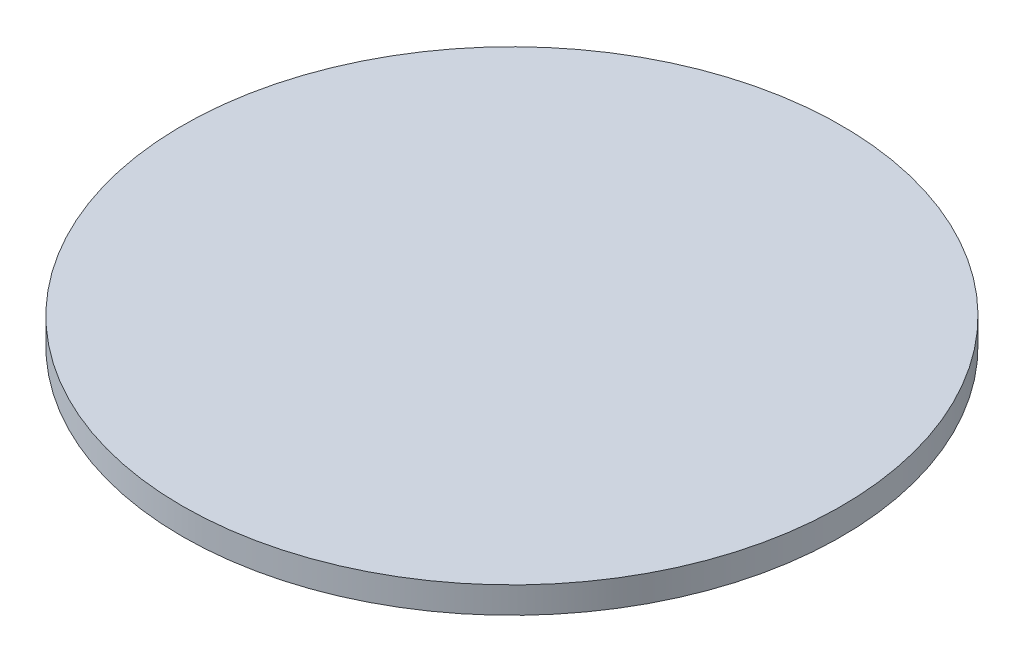
SolidWorks part; units mm, degrees
ref_plane "Front Plane" through (0, 0, 0) normal (0, 0, 1) x (1, 0, 0)
ref_plane "Top Plane" through (0, 0, 0) normal (0, 1, 0) x (1, 0, 0)
ref_plane "Right Plane" through (0, 0, 0) normal (1, 0, 0) x (0, 0, -1)
sketch "Sketch1" plane through (0, 0, 0) normal (0, 1, 0) x (1, 0, 0)
  circle A0 centre (0, 0) radius 25
  dimension "D1" = 50
extrude "Boss-Extrude1" add sketch "Sketch1" along normal blind 70 contours A0
ref_plane "Plane1" through (0, 40, 0) normal (0, 1, 0) x (1, 0, 0)
sketch "Sketch2" plane through (0, 40, 0) normal (0, 1, 0) x (1, 0, 0)
  arc A0 (-49.7681, -4.8103) -> (-49.9259, 2.7205) centre (0, 0) ccw
  arc A1 (-49.9259, 2.7205) -> (-49.7681, -4.8103) centre (-74.5563, -1.5629) ccw
  point P5 (0, 0)
  point P6 (0, 0)
  point P7 (-74.5563, -1.5629)
  dimension "D1" = 100
  dimension "D2" = 50
extrude "Boss-Extrude2" add sketch "Sketch2" along normal blind 5
ref_plane "Plane2" through (0, 70, 0) normal (0, 1, 0) x (1, 0, 0)
sketch "Sketch3" plane through (0, 70, 0) normal (0, 1, 0) x (1, 0, 0)
  circle A0 centre (0, 0) radius 125
  dimension "D1" = 250
extrude "Boss-Extrude3" add sketch "Sketch3" along normal blind 10 contours A0
